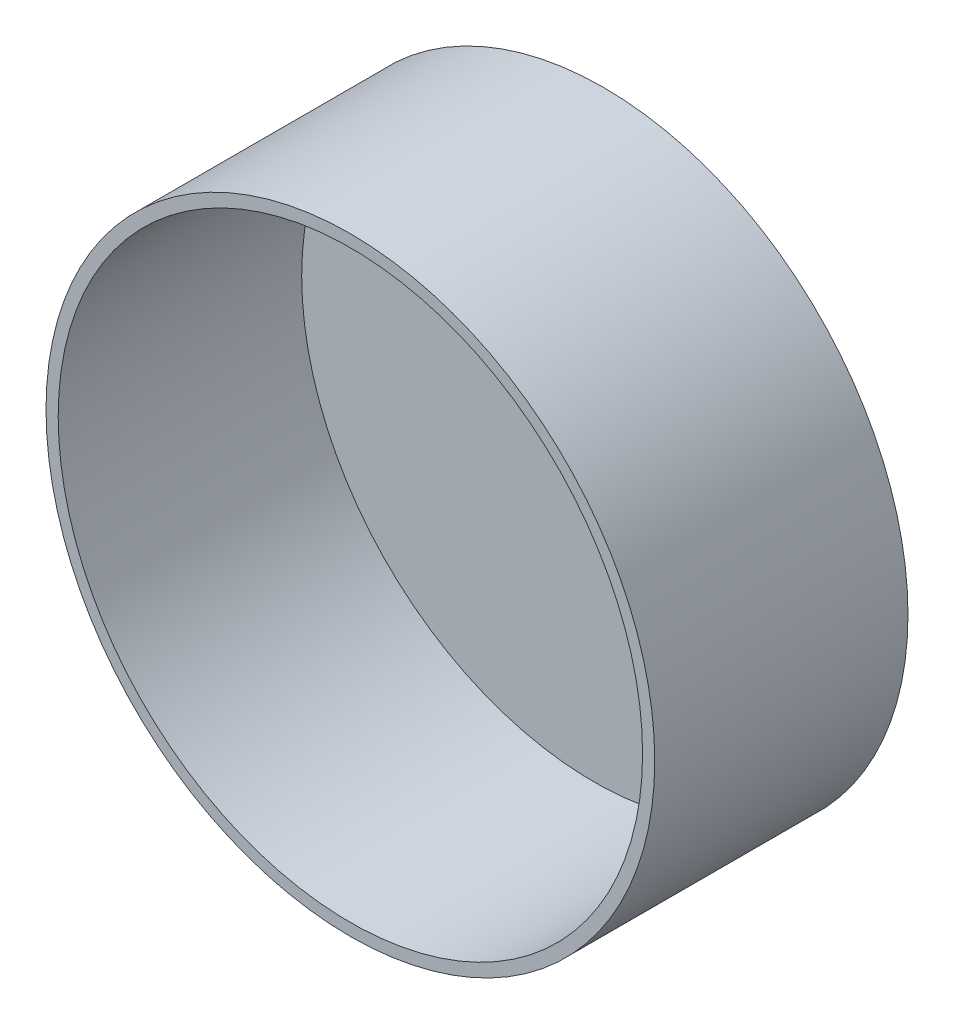
SolidWorks part; units mm, degrees
ref_plane "Front Plane" through (0, 0, 0) normal (0, 0, 1) x (1, 0, 0)
ref_plane "Top Plane" through (0, 0, 0) normal (0, 1, 0) x (1, 0, 0)
ref_plane "Right Plane" through (0, 0, 0) normal (1, 0, 0) x (0, 0, -1)
sketch "Sketch1" plane through (0, 0, 0) normal (0, 0, 1) x (1, 0, 0)
  circle A0 centre (0, 0) radius 125
  dimension "D1" = 250
extrude "Boss-Extrude1" add sketch "Sketch1" along normal blind 4
sketch "Sketch2" plane through (0, 0, 4) normal (0, 0, 1) x (1, 0, 0)
  circle A0 centre (0, 0) radius 120
  circle A1 centre (0, 0) radius 125 construction
  circle A2 centre (0, 0) radius 125
  dimension "D1" = 240
extrude "Boss-Extrude2" add sketch "Sketch2" along normal blind 100
